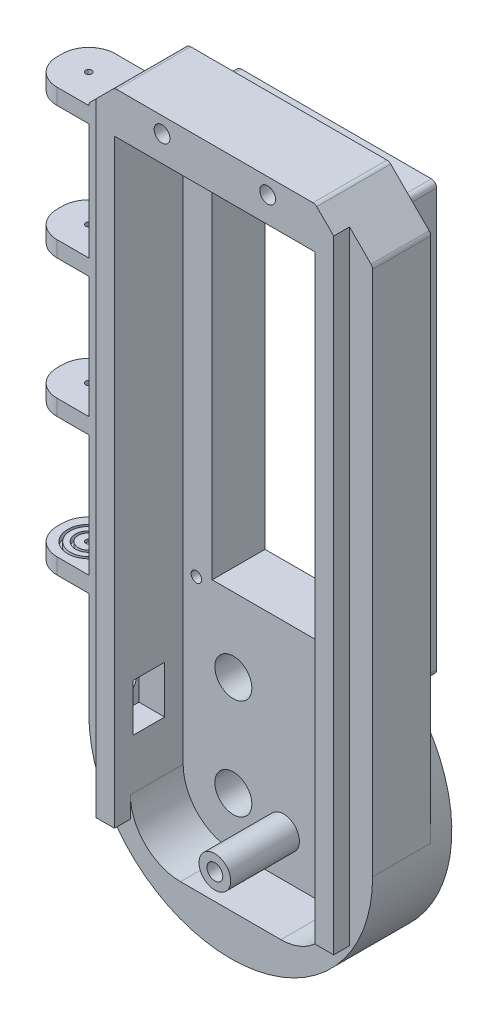
SolidWorks part; units mm, degrees
ref_plane "Alzado" through (0, 0, 0) normal (0, 0, 1) x (1, 0, 0)
ref_plane "Planta" through (0, 0, 0) normal (0, 1, 0) x (1, 0, 0)
ref_plane "Vista lateral" through (0, 0, 0) normal (1, 0, 0) x (0, 0, -1)
sketch "Croquis1" plane through (0, 0, 0) normal (0, 0, 1) x (1, 0, 0)
  line L1 (-19, -40.5) -> (19, -40.5)
  line L2 (-19, -40.5) -> (-19, 40.5)
  line L3 (-19, 40.5) -> (19, 40.5)
  line L4 (19, -40.5) -> (19, 40.5)
  line L5 (-19, -40.5) -> (19, 40.5) construction
  line L6 (-19, 40.5) -> (19, -40.5) construction
  line L7 (-19, -40.5) -> (19, -40.5)
  line L8 (-19, -40.5) -> (-19, -78.5)
  line L9 (-19, -78.5) -> (19, -78.5)
  line L10 (19, -40.5) -> (19, -78.5)
  line L13 (-13.5, 36) -> (13.5, 36)
  line L28 (13.5, 36) -> (13.5, -36)
  line L29 (-13.5, 36) -> (-13.5, -36)
  line L30 (-13.5, -36) -> (13.5, -36)
  circle A0 centre (-9.5, -50) radius 3.5
  circle A1 centre (9.5, -59.5) radius 3.5
  circle A2 centre (-9.5, -69) radius 3.5
  arc A3 (19, -40.5) -> (-19, -40.5) centre (0, -59.5) cw
  point P0 (0, 0)
  point P27 (9.5, -63)
  point P30 (9.5, -54.5)
  point P34 (-13.5, 0)
extrude "Saliente-Extruir1" add sketch "Croquis1" along normal blind 5 contours L1 L4 L3 L2 L30 L29 L13 L28 | L10 L1 L8 L9 A2 A1 A0 | A3 L10 | A3 L9 | A3 L8
sketch "Croquis2" plane through (0, 0, 0) normal (0, 0, -1) x (-1, 0, 0)
  line L0 (-19, 40.5) -> (19, 40.5)
  line L1 (19, -40.5) -> (-19, -40.5)
  line L2 (-19, -40.5) -> (-19, 40.5)
  line L4 (19, -40.5) -> (19, 40.5)
  line L5 (-13.5, 36) -> (-13.5, -36)
  line L7 (-13.5, -36) -> (13.5, -36)
  line L8 (13.5, -36) -> (13.5, 36)
  line L9 (13.5, 36) -> (-13.5, 36)
extrude "Saliente-Extruir2" add sketch "Croquis2" along normal blind 5
sketch "Croquis3" plane through (0, 0, 5) normal (0, 0, 1) x (1, 0, 0)
  line L0 (26.8701, -59.5) -> (26.8701, 40.5)
  line L1 (19, -59.5) -> (19, 40.5)
  line L2 (19, 40.5) -> (-19, 40.5)
  line L3 (-19, 40.5) -> (-19, -59.5)
  line L4 (26.8701, 40.5) -> (19, 48.3701)
  line L5 (19, 48.3701) -> (-19, 48.3701)
  line L6 (-19, 48.3701) -> (-26.8701, 40.5)
  line L7 (-26.8701, 40.5) -> (-26.8701, -59.5)
  arc A2 (-19, -59.5) -> (19, -59.5) centre (0, -59.5) ccw
  arc A3 (-26.8701, -59.5) -> (26.8701, -59.5) centre (0, -59.5) ccw
extrude "Saliente-Extruir9" add sketch "Croquis3" against normal blind 1
sketch "Croquis4" plane through (0, 0, 4) normal (0, 0, -1) x (-1, 0, 0)
  line L0 (-19, 40.5) -> (-19, -40.5)
  line L1 (-19, 40.5) -> (19, 40.5)
  line L2 (19, 40.5) -> (19, -40.5)
  line L3 (14, -77) -> (-14, -77)
  line L4 (-19, -72) -> (-19, -41.338)
  line L5 (19, -72) -> (19, -40.5)
  line L6 (-26.8701, 40.5) -> (-19, 48.3701)
  line L7 (-19, 48.3701) -> (19, 48.3701)
  line L8 (19, 48.3701) -> (26.8701, 40.5)
  line L9 (26.8701, 40.5) -> (26.8701, -59.5)
  line L10 (-26.8701, 40.5) -> (-26.8701, -59.5)
  arc A0 (-19, -40.5) -> (-26.8701, -59.5) centre (0, -59.5) ccw construction
  arc A1 (-14, -77) -> (-19, -72) centre (-14, -72) cw
  arc A2 (14, -77) -> (19, -72) centre (14, -72) ccw
  arc A3 (-19, -40.5) -> (19, -40.5) centre (0, -59.5) ccw construction
  arc A4 (-26.8701, -59.5) -> (26.8701, -59.5) centre (0, -59.5) ccw
  arc M1 (19, -40.5) -> (26.8701, -59.5) centre (0, -59.5) cw
  line M2 (26.8701, -59.5) -> (26.8701, 40.5)
  line M3 (26.8701, 40.5) -> (19, 48.3701)
  line M4 (19, 48.3701) -> (-19, 48.3701)
  line M5 (-19, 48.3701) -> (-26.8701, 40.5)
  line M6 (-26.8701, 40.5) -> (-26.8701, -59.5)
  arc M7 (-26.8701, -59.5) -> (-19, -40.5) centre (0, -59.5) cw
  line M8 (-19, -40.5) -> (-19, 40.5)
  line M9 (-19, 40.5) -> (19, 40.5)
  line M10 (19, 40.5) -> (19, -40.5)
  dimension "D1" = 5
extrude "Saliente-Extruir10" add sketch "Croquis4" against normal blind 11 contours M10 M1 M2 M3 M4 M5 M6 M7 M8 M9
sketch "Croquis5" plane through (0, 0, 5) normal (0, 0, 1) x (1, 0, 0)
  line L0 (-19, -59.5) -> (-19, -69)
  line L1 (19, -69) -> (19, -59.5)
  line L2 (9.5, -78.5) -> (-9.5, -78.5)
  line L3 (19, -59.5) -> (19, -40.5)
  line L4 (-19, -59.5) -> (-19, -40.5)
  arc A0 (-19, -40.5) -> (19, -40.5) centre (0, -59.5) ccw
  arc A1 (-9.5, -78.5) -> (-19, -69) centre (-9.5, -69) cw
  arc A2 (9.5, -78.5) -> (19, -69) centre (9.5, -69) ccw
extrude "Saliente-Extruir11" add sketch "Croquis5" along normal blind 10
fillet "Redondeo1" radius 1 4 edges at (-19, -40.5, -2.5) (-19, 40.5, -0.5) (19, 40.5, -0.5) (19, -40.5, -2.5)
fillet "Redondeo2" radius 1 5 edges at (-18.7071, 40.2071, 4) (18.7071, 40.2071, 4) (-19, -0.5, 4) (0, 40.5, 4) (19, -0.5, 4)
fillet "Redondeo3" radius 1 4 edges at (-26.8701, 40.5, 9.5) (-19, 48.3701, 9.5) (26.8701, 40.5, 9.5) (19, 48.3701, 9.5)
sketch "Croquis6" plane through (-26.8701, 0, 0) normal (-1, 0, 0) x (0, 0, 1)
  line L2 (8.5, -50.5) -> (14.5, -50.5)
  line L3 (14.5, -50.5) -> (14.5, -59.5)
  line L4 (14.5, -59.5) -> (8.5, -59.5)
  line L5 (8.5, -50.5) -> (8.5, -59.5)
extrude "Cortar-Extruir1" cut sketch "Croquis6" against normal blind 8
sketch "Croquis7" plane through (-26.8701, 0, 0) normal (-1, 0, 0) x (0, 0, 1)
  line L0 (8.5, -50.5) -> (14.5, -50.5)
  line L1 (14.5, -50.5) -> (14.5, -59.5)
  line L2 (14.5, -59.5) -> (8.5, -59.5)
  line L3 (8.5, -59.5) -> (8.5, -50.5)
  circle A0 centre (11.5, -55) radius 2.5
extrude "Saliente-Extruir12" add sketch "Croquis7" against normal blind 3
sketch "Croquis8" plane through (-26.8701, 0, 0) normal (-1, 0, 0) x (0, 0, 1)
  line L0 (4, 40.0858) -> (4, 37.0858)
  line L1 (4, 39.5) -> (4, -41.5556) construction
  line L2 (4, 37.0858) -> (15, 37.0858)
  line L3 (15, -59.5) -> (15, 40.0858) construction
  line L4 (15, 37.0858) -> (15, 40.0858)
  line L5 (15, 40.0858) -> (4, 40.0858)
  line L6 (9.5, 37.0858) -> (9.5, 15.0858)
  line L7 (9.5, 15.0858) -> (15, 15.0858)
  line L8 (9.5, 15.0858) -> (4, 15.0858)
  line L9 (4, 15.0858) -> (4, 12.0858)
  line L10 (4, 40.0858) -> (4, -59.5) construction
  line L11 (4, 12.0858) -> (15, 12.0858)
  line L12 (15, 12.0858) -> (15, 15.0858)
  line L13 (9.5, 12.0858) -> (9.5, -10.9142)
  line L14 (9.5, -10.9142) -> (15, -10.9142)
  line L15 (15, -10.9142) -> (15, -13.9142)
  line L16 (15, -13.9142) -> (4, -13.9142)
  line L17 (4, -13.9142) -> (4, -10.9142)
  line L18 (4, -10.9142) -> (9.5, -10.9142)
  line L19 (9.5, -13.9142) -> (9.5, -36.9142)
  line L20 (9.5, -36.9142) -> (15, -36.9142)
  line L21 (15, -36.9142) -> (15, -39.9142)
  line L22 (15, -39.9142) -> (4, -39.9142)
  line L23 (4, -39.9142) -> (4, -36.9142)
  line L24 (4, -36.9142) -> (9.5, -36.9142)
  line M2 (15, -59.5) -> (15, 40.0858)
  line M3 (15, 40.0858) -> (4, 40.0858)
  line M4 (4, 40.0858) -> (4, -59.5)
extrude "Saliente-Extruir13" add sketch "Croquis8" along normal blind 11 contours L2 M4 M2 M3 | L11 L7 L8 M4 M2 | L18 L16 L14 M4 M2 | L24 L22 L20 M4 M2
fillet "Redondeo4" radius 5 8 edges at (-37.8701, -38.4142, 4) (-37.8701, -38.4142, 15) (-37.8701, -12.4142, 4) (-37.8701, -12.4142, 15) (-37.8701, 13.5858, 4) (-37.8701, 13.5858, 15) (-37.8701, 38.5858, 4) (-37.8701, 38.5858, 15)
sketch "Croquis9" plane through (0, 40.0858, 0) normal (0, 1, 0) x (1, 0, 0)
  circle A0 centre (-32.3701, -9.5) radius 0.6
extrude "Cortar-Extruir2" cut sketch "Croquis9" against normal blind 80
sketch "Croquis10" plane through (0, -39.9142, 0) normal (0, -1, 0) x (1, 0, 0)
  circle A0 centre (-32.3701, 9.5) radius 0.6
extrude "Saliente-Extruir14" add sketch "Croquis10" against normal blind 2.5
sketch "Croquis11" plane through (0, -36.9142, 0) normal (0, 1, 0) x (1, 0, 0)
  circle A0 centre (-32.3701, -9.5) radius 2
  circle A1 centre (-32.3701, -9.5) radius 2.5
  circle A2 centre (-32.3701, -9.5) radius 3.5
  circle A3 centre (-32.3701, -9.5) radius 4
extrude "Cortar-Extruir3" cut sketch "Croquis11" against normal blind 1 contours A3 A2 | A1 A0
sketch "Croquis13" plane through (0, 0, 15) normal (0, 0, 1) x (1, 0, 0)
  line L0 (19, 40.5) -> (22.5, 40.5)
  line L1 (19, -69) -> (22.5, -69)
  line L2 (22.5, -69) -> (22.5, 40.5)
  line L3 (19, -69) -> (19, 40.5)
  line L5 (22.5, 40.5) -> (22.5, 44.8701)
  line L6 (-19, -69) -> (-19, 40.5)
  line L7 (-22.5, -69) -> (-22.5, 40.5)
  line L8 (-19, -69) -> (-22.5, -69)
  line L9 (-19, 40.5) -> (-22.5, 40.5)
  line L10 (-19, -69) -> (-19, -65.5)
  line L12 (19, -65.5) -> (19, -69)
  line L13 (-22.5, 40.5) -> (-22.5, 44.8701)
  line L14 (-26.5772, 40.7929) -> (-19.2929, 48.0772) construction
  line L15 (-22.5, 44.8701) -> (-19.2929, 48.0772)
  line L16 (-18.5858, 48.3701) -> (18.5858, 48.3701)
  line L19 (22.5, 44.8701) -> (19.2929, 48.0772)
  arc A0 (-19.2929, 48.0772) -> (-18.5858, 48.3701) centre (-18.5858, 47.3701) cw
  arc A1 (19.2929, 48.0772) -> (18.5858, 48.3701) centre (18.5858, 47.3701) ccw
  line M1 (19, 40.5) -> (19, -69)
  line M5 (-19, -69) -> (-19, 40.5)
  line M6 (-19, 40.5) -> (19, 40.5)
  line M14 (26.5772, 40.7929) -> (19.2929, 48.0772)
  arc M15 (19.2929, 48.0772) -> (18.5858, 48.3701) centre (18.5858, 47.3701) ccw
  line M16 (18.5858, 48.3701) -> (-18.5858, 48.3701)
  arc M17 (-18.5858, 48.3701) -> (-19.2929, 48.0772) centre (-18.5858, 47.3701) ccw
  line M18 (-19.2929, 48.0772) -> (-26.5772, 40.7929)
extrude "Saliente-Extruir15" add sketch "Croquis13" along normal blind 3 contours L6 L9 L7 L8 M5 | L1 L2 L0 L3 M1 | L13 L9 L0 L5 M6 M14 M15 M16 M17 M18
sketch "Croquis14" plane through (0, 0, 4) normal (0, 0, -1) x (-1, 0, 0)
  circle A0 centre (10, 45.3701) radius 1.5
  circle A1 centre (-10, 45.3701) radius 1.5
extrude "Cortar-Extruir4" cut sketch "Croquis14" against normal blind 14
sketch "Croquis16" plane through (0, -69, 0) normal (0, -1, 0) x (-1, 0, 0)
  line L1 (22.5, -15) -> (19, -15)
  line L2 (22.5, -15) -> (22.5, -18)
  line L3 (22.5, -18) -> (19, -18)
  line L4 (-19, -15) -> (-22.5, -15)
  line L5 (-19, -15) -> (-19, -18)
  line L6 (-19, -18) -> (-22.5, -18)
  line L7 (-22.5, -15) -> (-22.5, -18)
  line L8 (19, -15) -> (19, -18)
extrude "Saliente-Extruir16" add sketch "Croquis16" along normal blind 4
sketch "Croquis25" plane through (0, 0, 18) normal (0, 0, 1) x (1, 0, 0)
  line L0 (-10, 45.3701) -> (10, 45.3701)
  line L1 (0, 45.3701) -> (0, -70.6299)
  circle A0 centre (0, -70.6299) radius 3
  circle A1 centre (0, -70.6299) radius 1.5
extrude "Saliente-Extruir21" add sketch "Croquis25" against normal blind 18
sketch "Croquis26" plane through (0, 0, 18) normal (0, 0, 1) x (1, 0, 0)
  circle A0 centre (0, -70.6299) radius 1.5
extrude "Cortar-Extruir7" cut sketch "Croquis26" against normal blind 18
sketch "Croquis28" plane through (0, 0, 5) normal (0, 0, 1) x (1, 0, 0)
  circle A0 centre (-16.5, 38) radius 1
  circle A1 centre (14.5, 38) radius 1
  circle A2 centre (14.5, -37) radius 1
  circle A3 centre (-16.5, -37) radius 1
extrude "Cortar-Extruir8" cut sketch "Croquis28" against normal blind 4
